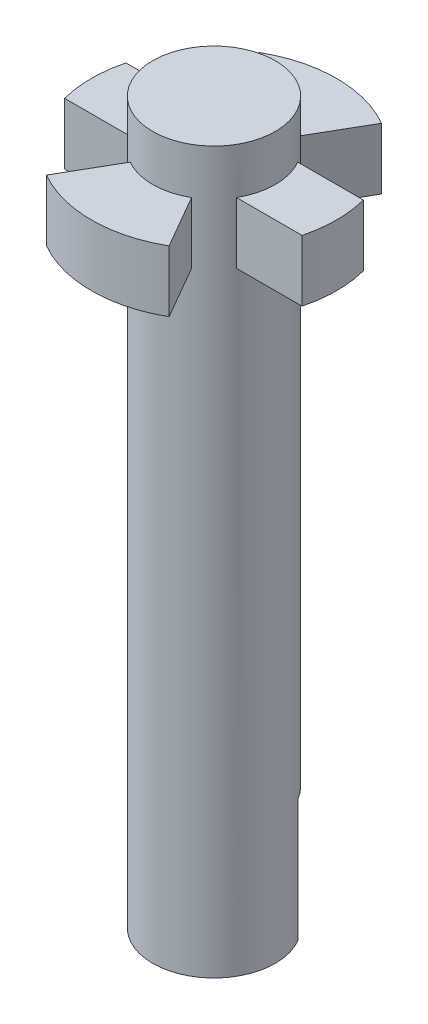
SolidWorks part; units mm, degrees
ref_plane "Front Plane" through (0, 0, 0) normal (0, 0, 1) x (1, 0, 0)
ref_plane "Top Plane" through (0, 0, 0) normal (0, 1, 0) x (1, 0, 0)
ref_plane "Right Plane" through (0, 0, 0) normal (1, 0, 0) x (0, 0, -1)
sketch "Sketch1" plane through (0, 0, 0) normal (0, 1, 0) x (1, 0, 0)
  circle A0 centre (0, 0) radius 4
  dimension "D1" = 8
extrude "Boss-Extrude1" add sketch "Sketch1" along normal blind 47
ref_plane "Plane1" through (0, 42, 0) normal (0, 1, 0) x (1, 0, 0)
sketch "Sketch2" plane through (0, 42, 0) normal (0, 1, 0) x (1, 0, 0)
  line L0 (-21.1894, 0) -> (0, 0) construction
  line L1 (0, -18.7506) -> (0, -4) construction
  line L2 (-4, 6.9282) -> (-2, 3.4641)
  line L3 (-7.746, 2) -> (-3.4641, 2)
  line L4 (7.746, 2) -> (3.4641, 2)
  line L5 (4, 6.9282) -> (2, 3.4641)
  line L6 (7.746, -2) -> (3.4641, -2)
  line L7 (-7.746, -2) -> (-3.4641, -2)
  line L8 (4, -6.9282) -> (2, -3.4641)
  line L9 (-4, -6.9282) -> (-2, -3.4641)
  line L10 (4, 0) -> (21.1894, 0) construction
  line L11 (0, 4) -> (0, 18.7506) construction
  arc A0 (-4, -6.9282) -> (4, -6.9282) centre (0, 0) ccw
  circle A1 centre (0, 0) radius 4 construction
  arc A2 (-7.746, 2) -> (-7.746, -2) centre (0, 0) ccw
  arc A3 (4, 6.9282) -> (-4, 6.9282) centre (0, 0) ccw
  arc A4 (7.746, -2) -> (7.746, 2) centre (0, 0) ccw
  arc A5 (3.4641, -2) -> (3.4641, 2) centre (0, 0) ccw
  arc A6 (-3.4641, 2) -> (-3.4641, -2) centre (0, 0) ccw
  arc A7 (-2, -3.4641) -> (2, -3.4641) centre (0, 0) ccw
  arc A8 (2, 3.4641) -> (-2, 3.4641) centre (0, 0) ccw
  point P6 (0, 0)
  point P9 (0, 0)
  dimension "D1" = 16
  dimension "D2" = 2
  dimension "D3" = 4
  dimension "D4" = 2
extrude "Boss-Extrude2" add sketch "Sketch2" along normal mid plane 4
sketch "Sketch3" plane through (0, 0, 0) normal (0, -1, 0) x (1, 0, 0)
  line L0 (-3.4641, -2) -> (3.4641, -2)
  circle A0 centre (0, 0) radius 4 construction
  arc A1 (-3.4641, -2) -> (3.4641, -2) centre (0, 0) ccw
  dimension "D1" = 2
extrude "Cut-Extrude1" cut sketch "Sketch3" against normal blind 8
